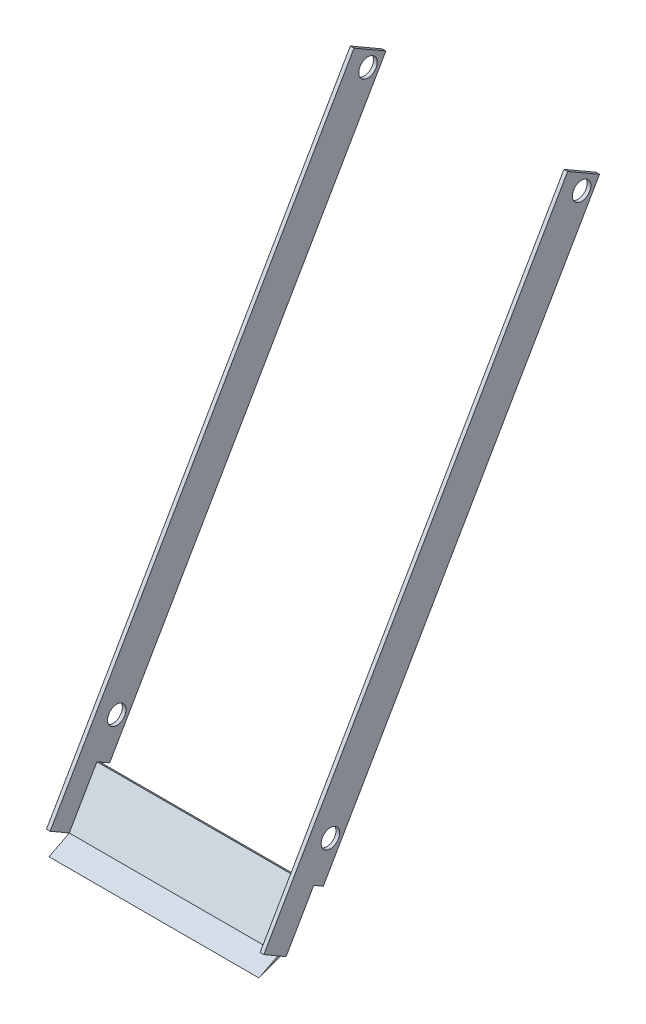
SolidWorks part; units mm, degrees
ref_plane "Front Plane" through (0, 0, 0) normal (0, 0, 1) x (1, 0, 0)
ref_plane "Top Plane" through (0, 0, 0) normal (0, 1, 0) x (1, 0, 0)
ref_plane "Right Plane" through (0, 0, 0) normal (1, 0, 0) x (0, 0, -1)
sketch "Sketch1" plane through (0, 0, 0) normal (1, 0, 0) x (0, 0, -1)
  line L0 (0, 0) -> (150, 259.8076) construction
  line L1 (0, 0) -> (0, -0.0547) construction
  line L2 (-0.0566, -0.022) -> (-30.0566, -51.9836) construction
  line L3 (0, 0) -> (-0.0566, -0.022) construction
  line L4 (158.6603, 254.8076) -> (141.3397, 264.8076)
  line L5 (141.3397, 264.8076) -> (-8.6839, 4.959)
  line L6 (158.6603, 254.8076) -> (8.6366, -5.041)
  line L7 (-0.0566, -0.022) -> (0, -0.0547)
  line L10 (-30.0566, -51.9836) -> (-234.0166, -51.9836) construction
  line L11 (-0.0566, -0.022) -> (-118.6405, -51.9836) construction
  line L12 (-8.6839, 4.959) -> (-118.6405, -51.9836)
  line L13 (8.6366, -5.041) -> (-118.6405, -51.9836)
  dimension "D1" = 300
  dimension "D2" = 10
  dimension "D3" = 60
extrude "Boss-Extrude1" add sketch "Sketch1" along normal blind 1140
sketch "Sketch2" plane through (1140, 0, 0) normal (1, 0, 0) x (0, 0, -1)
  line L0 (8.6366, -5.041) -> (158.6603, 254.8076)
  line L1 (8.6366, -5.041) -> (-112.607, 64.959)
  line L2 (-112.607, 64.959) -> (37.4167, 324.8076)
  line L3 (37.4167, 324.8076) -> (158.6603, 254.8076)
  dimension "D1" = 140
extrude "Boss-Extrude2" add sketch "Sketch2" along normal blind 20
sketch "Sketch3" plane through (0, 0, 0) normal (-1, 0, 0) x (0, 0, 1)
  line L0 (-158.6603, 254.8076) -> (-37.4167, 324.8076)
  line L1 (-37.4167, 324.8076) -> (112.607, 64.959)
  line L2 (112.607, 64.959) -> (-8.6366, -5.041)
  line L3 (-8.6366, -5.041) -> (-158.6603, 254.8076)
extrude "Boss-Extrude3" add sketch "Sketch3" along normal blind 20
sketch "Sketch4" plane through (0, 259.8076, -150) normal (0, 0.866, -0.5) x (1, 0, 0)
  line L0 (1140, -130) -> (1140, 10)
  line L1 (1140, 10) -> (1160, 10)
  line L2 (1160, 10) -> (1160, -130)
  line L3 (1160, -130) -> (1140, -130)
extrude "Boss-Extrude4" add sketch "Sketch4" along normal blind 2999.8
sketch "Sketch5" plane through (0, 259.8076, -150) normal (0, 0.866, -0.5) x (1, 0, 0)
  line L0 (-20, -130) -> (-20, 10)
  line L1 (-20, -130) -> (0, -130)
  line L2 (0, -130) -> (0, 10)
  line L3 (1140, 10) -> (-20, 10) construction
  line L4 (0, 10) -> (-20, 10)
extrude "Boss-Extrude5" add sketch "Sketch5" along normal blind 2999.8
sketch "Sketch7" plane through (0, -5, -8.6603) normal (0, -0.5, -0.866) x (-1, 0, 0)
  line L1 (-1160, 3299.8) -> (-1140, 3299.8)
  line L2 (-1160, 3299.8) -> (-1160, 300)
  line L3 (-1160, 300) -> (-1140, 300)
  line L4 (-1140, 3299.8) -> (-1140, 300)
extrude "Boss-Extrude6" add sketch "Sketch7" along normal blind 60
sketch "Sketch8" plane through (0, -5, -8.6603) normal (0, -0.5, -0.866) x (-1, 0, 0)
  line L0 (20, 3299.8) -> (20, -0.0474) construction
  line L1 (0, 3299.8) -> (20, 3299.8)
  line L2 (0, 3299.8) -> (0, 300)
  line L3 (0, 300) -> (20, 300)
  line L4 (20, 3299.8) -> (20, 300)
extrude "Boss-Extrude7" add sketch "Sketch8" along normal blind 60
sketch "Sketch10" plane through (1160, 0, 0) normal (1, 0, 0) x (0, 0, -1)
  line L0 (210.6218, 224.8076) -> (150, 259.8076)
  line L1 (150, 259.8076) -> (1907.7453, 3304.3118)
  line L2 (1710.5218, 2822.7106) -> (210.6218, 224.8076) construction
  line L3 (1537.3167, 2922.7106) -> (1710.5218, 2822.7106) construction
  circle A0 centre (249.2, 431.6271) radius 50
  circle A1 centre (1613.2, 2794.1444) radius 50
  dimension "D2" = 100
  dimension "D4" = 100
  dimension "D1" = 70
  dimension "D3" = 198.4
  dimension "D5" = 73.4
extrude "Cut-Extrude3" cut sketch "Sketch10" against normal through all contours L1 A0 | L1 A0 | L1 A1 | L1 A1
